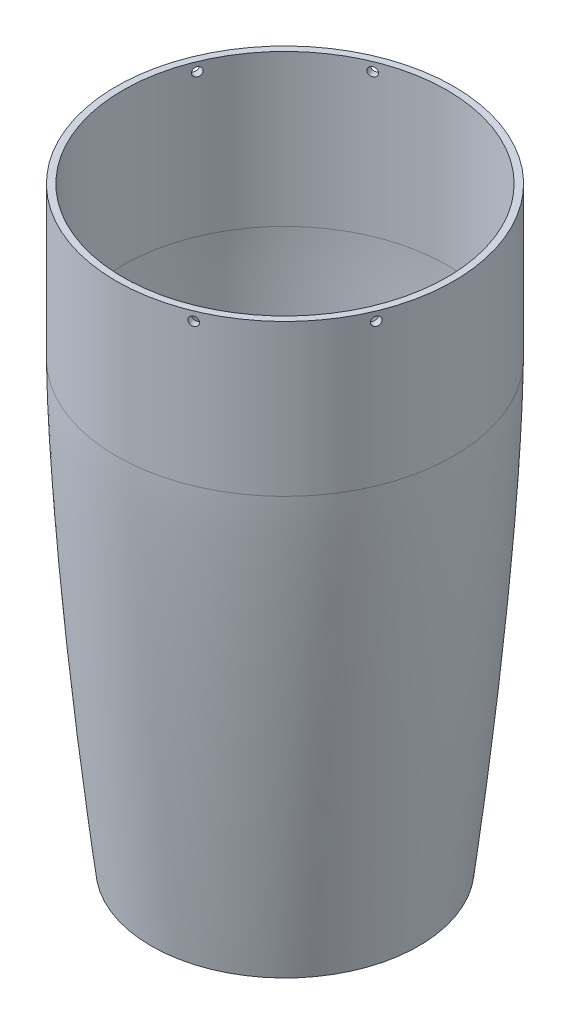
SolidWorks part; units mm, degrees
ref_plane "Front Plane" through (0, 0, 0) normal (0, 0, 1) x (1, 0, 0)
ref_plane "Top Plane" through (0, 0, 0) normal (0, 1, 0) x (1, 0, 0)
ref_plane "Right Plane" through (0, 0, 0) normal (1, 0, 0) x (0, 0, -1)
sketch "Sketch1" plane through (0, 0, 0) normal (0, 0, 1) x (1, 0, 0)
  line L20 (0, 0) -> (0, 581.1696) construction
  line L21 (76, 500) -> (73, 500) construction
  line L22 (0, 0) -> (0, 4.7311)
  line L23 (0, -55) -> (0, 55) construction
  line L24 (59.026, 315.99) -> (62.026, 315.99) construction
  line L25 (76, 500) -> (76, 560.25)
  line L26 (76, 560.25) -> (76, 568.25)
  line L27 (73, 500) -> (73, 568.25)
  line L28 (73, 568.25) -> (76, 568.25)
  line L29 (57.2723, 300.99) -> (60.2723, 300.99)
  spline S0 degree 4 poles (0, 0) (0.0138, 0.0035) (0.0403, 0.0132) (0.0896, 0.0421) (0.1748, 0.1033) (0.2791, 0.1957) (0.3945, 0.3129) (0.5113, 0.4445) (0.662, 0.6264) (0.8743, 0.9054) (1.2103, 1.3931) (1.7479, 2.2715) (2.5811, 3.8159) (3.9077, 6.6298) (5.9906, 11.7322) (8.9748, 20.2155) (12.4921, 31.7245) (16.2812, 45.6068) (21.0209, 64.6514) (26.2066, 87.6584) (31.7463, 114.7224) (37.5379, 145.854) (42.8718, 177.0669) (47.8072, 208.3451) (52.3812, 239.6781) (56.6152, 271.0588) (60.5197, 302.4822) (63.6484, 330.0118) (66.1189, 353.6316) (68.0301, 373.3295) (69.4668, 389.0964) (70.8061, 404.872) (71.887, 418.6831) (72.7427, 430.5264) (73.4044, 440.3994) (73.9011, 448.3) (74.3048, 455.2148) (74.6268, 461.1432) (74.8778, 466.0844) (75.0676, 470.0378) (75.3363, 476.0055) (75.5634, 481.7365) (75.7481, 487.2308) (75.8847, 492.4881) (75.9403, 495.117) (75.978, 497.3706) (75.9936, 498.8731) (76, 499.6244) (76, 500) knots 0 0 0 0 0 0.000112 0.000223 0.000447 0.000827 0.001207 0.00152 0.001832 0.002688 0.003968 0.006183 0.009943 0.016507 0.028468 0.049587 0.080772 0.111303 0.141834 0.204204 0.266574 0.328944 0.391314 0.453684 0.516055 0.578425 0.640795 0.703165 0.73435 0.765535 0.79672 0.827905 0.85909 0.874683 0.890275 0.905868 0.92146 0.929257 0.937053 0.944849 0.952645 0.976323 0.982242 0.988161 0.994081 0.99704 1 1 1 1 1 construction
  spline S1 degree 4 poles (0, 0) (0.0138, 0.0035) (0.0403, 0.0132) (0.0896, 0.0421) (0.1748, 0.1033) (0.2791, 0.1957) (0.3945, 0.3129) (0.5113, 0.4445) (0.662, 0.6264) (0.8743, 0.9054) (1.2103, 1.3931) (1.7479, 2.2715) (2.5811, 3.8159) (3.9077, 6.6298) (5.9906, 11.7322) (8.9748, 20.2155) (12.4921, 31.7245) (16.2812, 45.6068) (21.0209, 64.6514) (26.2066, 87.6584) (31.7463, 114.7224) (37.5379, 145.854) (42.8718, 177.0669) (47.8072, 208.3451) (52.3812, 239.6781) (56.6152, 271.0588) (60.5197, 302.4822) (63.6484, 330.0118) (66.1189, 353.6316) (68.0301, 373.3295) (69.4668, 389.0964) (70.8061, 404.872) (71.887, 418.6831) (72.7427, 430.5264) (73.4044, 440.3994) (73.9011, 448.3) (74.3048, 455.2148) (74.6268, 461.1432) (74.8778, 466.0844) (75.0676, 470.0378) (75.3363, 476.0055) (75.5634, 481.7365) (75.7481, 487.2308) (75.8847, 492.4881) (75.9403, 495.117) (75.978, 497.3706) (75.9936, 498.8731) (76, 499.6244) (76, 500) knots 0 0 0 0 0 0.000112 0.000223 0.000447 0.000827 0.001207 0.00152 0.001832 0.002688 0.003968 0.006183 0.009943 0.016507 0.028468 0.049587 0.080772 0.111303 0.141834 0.204204 0.266574 0.328944 0.391314 0.453684 0.516055 0.578425 0.640795 0.703165 0.73435 0.765535 0.79672 0.827905 0.85909 0.874683 0.890275 0.905868 0.92146 0.929257 0.937053 0.944849 0.952645 0.976323 0.982242 0.988161 0.994081 0.99704 1 1 1 1 1
  spline S2 degree 4 poles (-3, 0) (-2.9862, 0.0035) (-2.9597, 0.0132) (-2.9104, 0.0421) (-2.8252, 0.1033) (-2.7209, 0.1957) (-2.6055, 0.3129) (-2.4887, 0.4445) (-2.338, 0.6264) (-2.1257, 0.9054) (-1.7897, 1.3931) (-1.2521, 2.2715) (-0.4189, 3.8159) (0.9077, 6.6298) (2.9906, 11.7322) (5.9748, 20.2155) (9.4921, 31.7245) (13.2812, 45.6068) (18.0209, 64.6514) (23.2066, 87.6584) (28.7463, 114.7224) (34.5379, 145.854) (39.8718, 177.0669) (44.8072, 208.3451) (49.3812, 239.6781) (53.6152, 271.0588) (57.5197, 302.4822) (60.6484, 330.0118) (63.1189, 353.6316) (65.0301, 373.3295) (66.4668, 389.0964) (67.8061, 404.872) (68.887, 418.6831) (69.7427, 430.5264) (70.4044, 440.3994) (70.9011, 448.3) (71.3048, 455.2148) (71.6268, 461.1432) (71.8778, 466.0844) (72.0676, 470.0378) (72.3363, 476.0055) (72.5634, 481.7365) (72.7481, 487.2308) (72.8847, 492.4881) (72.9403, 495.117) (72.978, 497.3706) (72.9936, 498.8731) (73, 499.6244) (73, 500) knots 0 0 0 0 0 0.000112 0.000223 0.000447 0.000827 0.001207 0.00152 0.001832 0.002688 0.003968 0.006183 0.009943 0.016507 0.028468 0.049587 0.080772 0.111303 0.141834 0.204204 0.266574 0.328944 0.391314 0.453684 0.516055 0.578425 0.640795 0.703165 0.73435 0.765535 0.79672 0.827905 0.85909 0.874683 0.890275 0.905868 0.92146 0.929257 0.937053 0.944849 0.952645 0.976323 0.982242 0.988161 0.994081 0.99704 1 1 1 1 1 construction
  spline S3 degree 4 poles (-3, 0) (-2.9862, 0.0035) (-2.9597, 0.0132) (-2.9104, 0.0421) (-2.8252, 0.1033) (-2.7209, 0.1957) (-2.6055, 0.3129) (-2.4887, 0.4445) (-2.338, 0.6264) (-2.1257, 0.9054) (-1.7897, 1.3931) (-1.2521, 2.2715) (-0.4189, 3.8159) (0.9077, 6.6298) (2.9906, 11.7322) (5.9748, 20.2155) (9.4921, 31.7245) (13.2812, 45.6068) (18.0209, 64.6514) (23.2066, 87.6584) (28.7463, 114.7224) (34.5379, 145.854) (39.8718, 177.0669) (44.8072, 208.3451) (49.3812, 239.6781) (53.6152, 271.0588) (57.5197, 302.4822) (60.6484, 330.0118) (63.1189, 353.6316) (65.0301, 373.3295) (66.4668, 389.0964) (67.8061, 404.872) (68.887, 418.6831) (69.7427, 430.5264) (70.4044, 440.3994) (70.9011, 448.3) (71.3048, 455.2148) (71.6268, 461.1432) (71.8778, 466.0844) (72.0676, 470.0378) (72.3363, 476.0055) (72.5634, 481.7365) (72.7481, 487.2308) (72.8847, 492.4881) (72.9403, 495.117) (72.978, 497.3706) (72.9936, 498.8731) (73, 499.6244) (73, 500) knots 0 0 0 0 0 0.000112 0.000223 0.000447 0.000827 0.001207 0.00152 0.001832 0.002688 0.003968 0.006183 0.009943 0.016507 0.028468 0.049587 0.080772 0.111303 0.141834 0.204204 0.266574 0.328944 0.391314 0.453684 0.516055 0.578425 0.640795 0.703165 0.73435 0.765535 0.79672 0.827905 0.85909 0.874683 0.890275 0.905868 0.92146 0.929257 0.937053 0.944849 0.952645 0.976323 0.982242 0.988161 0.994081 0.99704 1 1 1 1 1
  dimension "D1" = 3
  dimension "D2" = 315.99
  dimension "D3" = 60.25
  dimension "D4" = 8
  dimension "D5" = 15
  dimension "D6" = 300.99
sketch "Sketch2" plane through (0, 0, 0) normal (0, 0, 1) x (1, 0, 0)
  line L0 (-70, 560.25) -> (70, 560.25)
  line L1 (70, 560.25) -> (70, 538.25)
  line L2 (70, 538.25) -> (44.45, 538.25)
  line L3 (44.45, 538.25) -> (44.45, 381.75)
  line L4 (44.45, 381.75) -> (60, 381.75)
  line L5 (60, 381.75) -> (60, 352.78)
  line L6 (60, 352.78) -> (32.43, 352.78)
  line L7 (32.43, 352.78) -> (32.43, 315.99)
  line L8 (32.43, 315.99) -> (-32.43, 315.99)
  line L9 (-32.43, 315.99) -> (-32.43, 352.78)
  line L10 (-32.43, 352.78) -> (-60, 352.78)
  line L11 (-60, 352.78) -> (-60, 381.75)
  line L12 (-60, 381.75) -> (-44.45, 381.75)
  line L13 (-44.45, 381.75) -> (-44.45, 538.25)
  line L14 (-44.45, 538.25) -> (-70, 538.25)
  line L15 (-70, 538.25) -> (-70, 560.25)
  line L16 (0, 315.99) -> (0, 560.25)
  line L17 (0, 0) -> (0, 781.6146) construction
  line L18 (0, 0) -> (0, 581.1696) construction
  line L19 (60, 352.78) -> (63, 352.78) construction
  spline S1 degree 4 poles (-3, 0) (-2.9862, 0.0035) (-2.9597, 0.0132) (-2.9104, 0.0421) (-2.8252, 0.1033) (-2.7209, 0.1957) (-2.6055, 0.3129) (-2.4887, 0.4445) (-2.338, 0.6264) (-2.1257, 0.9054) (-1.7897, 1.3931) (-1.2521, 2.2715) (-0.4189, 3.8159) (0.9077, 6.6298) (2.9906, 11.7322) (5.9748, 20.2155) (9.4921, 31.7245) (13.2812, 45.6068) (18.0209, 64.6514) (23.2066, 87.6584) (28.7463, 114.7224) (34.5379, 145.854) (39.8718, 177.0669) (44.8072, 208.3451) (49.3812, 239.6781) (53.6152, 271.0588) (57.5197, 302.4822) (60.6484, 330.0118) (63.1189, 353.6316) (65.0301, 373.3295) (66.4668, 389.0964) (67.8061, 404.872) (68.887, 418.6831) (69.7427, 430.5264) (70.4044, 440.3994) (70.9011, 448.3) (71.3048, 455.2148) (71.6268, 461.1432) (71.8778, 466.0844) (72.0676, 470.0378) (72.3363, 476.0055) (72.5634, 481.7365) (72.7481, 487.2308) (72.8847, 492.4881) (72.9403, 495.117) (72.978, 497.3706) (72.9936, 498.8731) (73, 499.6244) (73, 500) knots 0 0 0 0 0 0.000112 0.000223 0.000447 0.000827 0.001207 0.00152 0.001832 0.002688 0.003968 0.006183 0.009943 0.016507 0.028468 0.049587 0.080772 0.111303 0.141834 0.204204 0.266574 0.328944 0.391314 0.453684 0.516055 0.578425 0.640795 0.703165 0.73435 0.765535 0.79672 0.827905 0.85909 0.874683 0.890275 0.905868 0.92146 0.929257 0.937053 0.944849 0.952645 0.976323 0.982242 0.988161 0.994081 0.99704 1 1 1 1 1 construction
  point P5 (0, 315.99)
  dimension "D1" = 140
  dimension "D2" = 88.9
  dimension "D3" = 120
  dimension "D4" = 64.86
  dimension "D5" = 22
  dimension "D6" = 156.5
  dimension "D7" = 28.97
  dimension "D8" = 36.79
  dimension "D9" = 3
  dimension "D10" = 315.99
  dimension "D11" = 60.25
revolve "Revolve1" [suppressed] add sketch "Sketch2" angle 360 about L16
revolve "Revolve2" add sketch "Sketch1" angle 360 about L20
ref_plane "Plane1" through (0, 564.25, 0) normal (0, 1, 0) x (1, 0, 0)
sketch "Sketch3" plane through (0, 564.25, 0) normal (0, 1, 0) x (1, 0, 0)
  line L0 (0, 79.8614) -> (0, 0) construction
  line L1 (-57.3979, -57.3979) -> (58.2472, 58.2472) construction
  line L2 (-33.3198, 80.4411) -> (38.5393, -93.0422) construction
  line L3 (-96.5536, 39.9938) -> (89.9659, -37.2651) construction
  dimension "D1" = 45
  dimension "D2" = 22.5
  dimension "D3" = 45
ref_plane "Plane2" through (-53.7401, 0, 53.7401) normal (-0.7071, 0, 0.7071) x (0.7071, 0, 0.7071)
ref_plane "Plane3" through (-70.2148, 0, -29.0839) normal (-0.9239, 0, -0.3827) x (-0.3827, 0, 0.9239)
ref_plane "Plane4" through (-29.0839, 0, -70.2148) normal (-0.3827, 0, -0.9239) x (-0.9239, 0, 0.3827)
sketch "Sketch4" plane through (-53.7401, 0, 53.7401) normal (-0.7071, 0, 0.7071) x (0.7071, 0, 0.7071)
  circle A0 centre (0, 564.25) radius 2
  dimension "D1" = 4
sketch "Sketch5" plane through (-70.2148, 0, -29.0839) normal (-0.9239, 0, -0.3827) x (-0.3827, 0, 0.9239)
  circle A0 centre (0, 564.25) radius 2
  dimension "D1" = 4
sketch "Sketch6" plane through (-29.0839, 0, -70.2148) normal (-0.3827, 0, -0.9239) x (-0.9239, 0, 0.3827)
  circle A0 centre (0, 564.25) radius 2
  dimension "D1" = 4
extrude "Cut-Extrude1" cut sketch "Sketch4" against normal through all
extrude "Cut-Extrude2" cut sketch "Sketch5" against normal through all
extrude "Cut-Extrude3" cut sketch "Sketch6" against normal through all
equation "\"Length\"= 500"
equation "\"Radius\"= 76"
